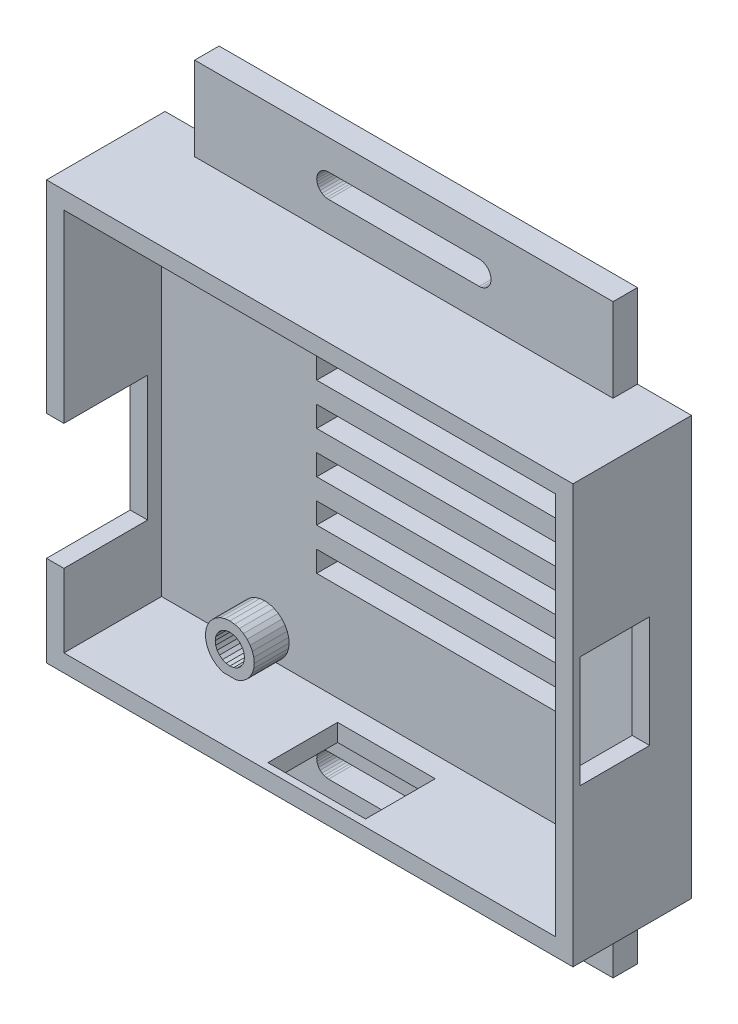
SolidWorks part; units mm, degrees
ref_plane "Front Plane" through (0, 0, 0) normal (0, 0, 1) x (1, 0, 0)
ref_plane "Top Plane" through (0, 0, 0) normal (0, 1, 0) x (1, 0, 0)
ref_plane "Right Plane" through (0, 0, 0) normal (1, 0, 0) x (0, 0, -1)
ref_plane "Plane1" through (0, 0, 0) normal (0, 0, -1) x (-1, 0, 0)
sketch "Sketch1" plane through (0, 0, 0) normal (0, 0, -1) x (-1, 0, 0)
  line L0 (37.75, 30) -> (-37.75, 30)
  line L1 (-37.75, 30) -> (-37.75, -30)
  line L2 (-37.75, -30) -> (37.75, -30)
  line L3 (37.75, -30) -> (37.75, 30)
extrude "Boss-Extrude1" add sketch "Sketch1" against normal blind 17
sketch "Sketch2" plane through (0, 0, 17) normal (0, 0, 1) x (1, 0, 0)
  line L0 (-35.25, -27.5) -> (35.25, -27.5)
  line L1 (35.25, -27.5) -> (35.25, 27.5)
  line L2 (35.25, 27.5) -> (-35.25, 27.5)
  line L3 (-35.25, 27.5) -> (-35.25, -27.5)
extrude "Cut-Extrude1" cut sketch "Sketch2" against normal blind 14
sketch "Sketch3" plane through (-37.75, 0, 0) normal (-1, 0, 0) x (0, 0, 1)
  line L0 (17, -17) -> (17, 1)
  line L1 (17, 1) -> (5, 1)
  line L2 (5, 1) -> (5, -17)
  line L3 (5, -17) -> (17, -17)
extrude "Cut-Extrude2" cut sketch "Sketch3" against normal up to next
sketch "Sketch4" plane through (0, 30, 0) normal (0, 1, 0) x (-1, 0, 0)
  line L0 (-30, 3.5) -> (30, 3.5)
  line L1 (30, 3.5) -> (30, 0)
  line L2 (30, 0) -> (-30, 0)
  line L3 (-30, 0) -> (-30, 3.5)
extrude "Boss-Extrude2" add sketch "Sketch4" along normal blind 12
sketch "Sketch5" plane through (0, 0, 3.5) normal (0, 0, 1) x (1, 0, 0)
  line L0 (12.3706, 36.6506) -> (12.2135, 36.9445)
  line L1 (12.2135, 36.9445) -> (12.0021, 37.2021)
  line L2 (12.0021, 37.2021) -> (11.7445, 37.4135)
  line L3 (11.7445, 37.4135) -> (11.4506, 37.5706)
  line L4 (11.4506, 37.5706) -> (11.1317, 37.6673)
  line L5 (11.1317, 37.6673) -> (10.8, 37.7)
  line L6 (10.8, 37.7) -> (-10.8, 37.7)
  line L7 (-10.8, 37.7) -> (-11.1317, 37.6673)
  line L8 (-11.1317, 37.6673) -> (-11.4506, 37.5706)
  line L9 (-11.4506, 37.5706) -> (-11.7445, 37.4135)
  line L10 (-11.7445, 37.4135) -> (-12.0021, 37.2021)
  line L11 (-12.0021, 37.2021) -> (-12.2135, 36.9445)
  line L12 (-12.2135, 36.9445) -> (-12.3706, 36.6506)
  line L13 (-12.3706, 36.6506) -> (-12.4673, 36.3317)
  line L14 (-12.4673, 36.3317) -> (-12.5, 36)
  line L15 (-12.5, 36) -> (-12.4673, 35.6683)
  line L16 (-12.4673, 35.6683) -> (-12.3706, 35.3494)
  line L17 (-12.3706, 35.3494) -> (-12.2135, 35.0555)
  line L18 (-12.2135, 35.0555) -> (-12.0021, 34.7979)
  line L19 (-12.0021, 34.7979) -> (-11.7445, 34.5865)
  line L20 (-11.7445, 34.5865) -> (-11.4506, 34.4294)
  line L21 (-11.4506, 34.4294) -> (-11.1317, 34.3327)
  line L22 (-11.1317, 34.3327) -> (-10.8, 34.3)
  line L23 (-10.8, 34.3) -> (10.8, 34.3)
  line L24 (10.8, 34.3) -> (11.1317, 34.3327)
  line L25 (11.1317, 34.3327) -> (11.4506, 34.4294)
  line L26 (11.4506, 34.4294) -> (11.7445, 34.5865)
  line L27 (11.7445, 34.5865) -> (12.0021, 34.7979)
  line L28 (12.0021, 34.7979) -> (12.2135, 35.0555)
  line L29 (12.2135, 35.0555) -> (12.3706, 35.3494)
  line L30 (12.3706, 35.3494) -> (12.4673, 35.6683)
  line L31 (12.4673, 35.6683) -> (12.5, 36)
  line L32 (12.5, 36) -> (12.4673, 36.3317)
  line L33 (12.4673, 36.3317) -> (12.3706, 36.6506)
extrude "Cut-Extrude3" cut sketch "Sketch5" against normal through all
sketch "Sketch6" plane through (0, -30, 0) normal (0, -1, 0) x (1, 0, 0)
  line L0 (-30, 0) -> (-30, 3.5)
  line L1 (-30, 3.5) -> (30, 3.5)
  line L2 (30, 3.5) -> (30, 0)
  line L3 (30, 0) -> (-30, 0)
extrude "Boss-Extrude3" add sketch "Sketch6" along normal blind 12
sketch "Sketch7" plane through (0, 0, 3.5) normal (0, 0, 1) x (1, 0, 0)
  line L0 (12.5, -36) -> (12.4673, -35.6683)
  line L1 (12.4673, -35.6683) -> (12.3706, -35.3494)
  line L2 (12.3706, -35.3494) -> (12.2135, -35.0555)
  line L3 (12.2135, -35.0555) -> (12.0021, -34.7979)
  line L4 (12.0021, -34.7979) -> (11.7445, -34.5865)
  line L5 (11.7445, -34.5865) -> (11.4506, -34.4294)
  line L6 (11.4506, -34.4294) -> (11.1317, -34.3327)
  line L7 (11.1317, -34.3327) -> (10.8, -34.3)
  line L8 (10.8, -34.3) -> (-10.8, -34.3)
  line L9 (-10.8, -34.3) -> (-11.1317, -34.3327)
  line L10 (-11.1317, -34.3327) -> (-11.4506, -34.4294)
  line L11 (-11.4506, -34.4294) -> (-11.7445, -34.5865)
  line L12 (-11.7445, -34.5865) -> (-12.0021, -34.7979)
  line L13 (-12.0021, -34.7979) -> (-12.2135, -35.0555)
  line L14 (-12.2135, -35.0555) -> (-12.3706, -35.3494)
  line L15 (-12.3706, -35.3494) -> (-12.4673, -35.6683)
  line L16 (-12.4673, -35.6683) -> (-12.5, -36)
  line L17 (-12.5, -36) -> (-12.4673, -36.3317)
  line L18 (-12.4673, -36.3317) -> (-12.3706, -36.6506)
  line L19 (-12.3706, -36.6506) -> (-12.2135, -36.9445)
  line L20 (-12.2135, -36.9445) -> (-12.0021, -37.2021)
  line L21 (-12.0021, -37.2021) -> (-11.7445, -37.4135)
  line L22 (-11.7445, -37.4135) -> (-11.4506, -37.5706)
  line L23 (-11.4506, -37.5706) -> (-11.1317, -37.6673)
  line L24 (-11.1317, -37.6673) -> (-10.8, -37.7)
  line L25 (-10.8, -37.7) -> (10.8, -37.7)
  line L26 (10.8, -37.7) -> (11.1317, -37.6673)
  line L27 (11.1317, -37.6673) -> (11.4506, -37.5706)
  line L28 (11.4506, -37.5706) -> (11.7445, -37.4135)
  line L29 (11.7445, -37.4135) -> (12.0021, -37.2021)
  line L30 (12.0021, -37.2021) -> (12.2135, -36.9445)
  line L31 (12.2135, -36.9445) -> (12.3706, -36.6506)
  line L32 (12.3706, -36.6506) -> (12.4673, -36.3317)
  line L33 (12.4673, -36.3317) -> (12.5, -36)
extrude "Cut-Extrude4" cut sketch "Sketch7" against normal through all
sketch "Sketch8" plane through (0, 0, 3) normal (0, 0, 1) x (1, 0, 0)
  line L0 (-13, 19.5) -> (-13, 16.5)
  line L1 (-13, 16.5) -> (23, 16.5)
  line L2 (23, 16.5) -> (23, 19.5)
  line L3 (23, 19.5) -> (-13, 19.5)
extrude "Cut-Extrude5" cut sketch "Sketch8" against normal through all
sketch "Sketch9" plane through (0, 0, 3) normal (0, 0, 1) x (1, 0, 0)
  line L0 (-13, -4.5) -> (-13, -7.5)
  line L1 (-13, -7.5) -> (23, -7.5)
  line L2 (23, -7.5) -> (23, -4.5)
  line L3 (23, -4.5) -> (-13, -4.5)
extrude "Cut-Extrude6" cut sketch "Sketch9" against normal through all
sketch "Sketch10" plane through (0, 0, 3) normal (0, 0, 1) x (1, 0, 0)
  line L0 (-13, 13.5) -> (-13, 10.5)
  line L1 (-13, 10.5) -> (23, 10.5)
  line L2 (23, 10.5) -> (23, 13.5)
  line L3 (23, 13.5) -> (-13, 13.5)
extrude "Cut-Extrude7" cut sketch "Sketch10" against normal through all
sketch "Sketch11" plane through (0, 0, 3) normal (0, 0, 1) x (1, 0, 0)
  line L0 (-13, 7.5) -> (-13, 4.5)
  line L1 (-13, 4.5) -> (23, 4.5)
  line L2 (23, 4.5) -> (23, 7.5)
  line L3 (23, 7.5) -> (-13, 7.5)
extrude "Cut-Extrude8" cut sketch "Sketch11" against normal through all
sketch "Sketch12" plane through (0, 0, 3) normal (0, 0, 1) x (1, 0, 0)
  line L0 (23, -13.5) -> (23, -10.5)
  line L1 (23, -10.5) -> (-13, -10.5)
  line L2 (-13, -10.5) -> (-13, -13.5)
  line L3 (-13, -13.5) -> (23, -13.5)
extrude "Cut-Extrude9" cut sketch "Sketch12" against normal through all
sketch "Sketch13" plane through (0, 0, 3) normal (0, 0, 1) x (1, 0, 0)
  line L0 (23, 1.5) -> (-13, 1.5)
  line L1 (-13, 1.5) -> (-13, -1.5)
  line L2 (-13, -1.5) -> (23, -1.5)
  line L3 (23, -1.5) -> (23, 1.5)
extrude "Cut-Extrude10" cut sketch "Sketch13" against normal through all
sketch "Sketch14" plane through (35.25, 0, 0) normal (-1, 0, 0) x (0, 0, 1)
  line L0 (6, 8) -> (6, -8)
  line L1 (6, -8) -> (16, -8)
  line L2 (16, -8) -> (16, 8)
  line L3 (16, 8) -> (6, 8)
extrude "Cut-Extrude11" cut sketch "Sketch14" against normal through all
sketch "Sketch15" plane through (0, -30, 0) normal (0, -1, 0) x (1, 0, 0)
  line L0 (7, 16) -> (-7, 16)
  line L1 (-7, 16) -> (-7, 6)
  line L2 (-7, 6) -> (7, 6)
  line L3 (7, 6) -> (7, 16)
extrude "Cut-Extrude12" cut sketch "Sketch15" against normal up to next
sketch "Sketch16" plane through (0, 0, 3) normal (0, 0, 1) x (1, 0, 0)
  line L0 (28.115, 8.89) -> (28.1823, 9.5728)
  line L1 (28.1823, 9.5728) -> (28.3814, 10.2294)
  line L2 (28.3814, 10.2294) -> (28.7049, 10.8345)
  line L3 (28.7049, 10.8345) -> (29.1401, 11.3649)
  line L4 (29.1401, 11.3649) -> (29.6705, 11.8001)
  line L5 (29.6705, 11.8001) -> (30.2756, 12.1236)
  line L6 (30.2756, 12.1236) -> (30.9322, 12.3227)
  line L7 (30.9322, 12.3227) -> (31.615, 12.39)
  line L8 (31.615, 12.39) -> (32.2978, 12.3227)
  line L9 (32.2978, 12.3227) -> (32.9544, 12.1236)
  line L10 (32.9544, 12.1236) -> (33.5595, 11.8001)
  line L11 (33.5595, 11.8001) -> (34.0899, 11.3649)
  line L12 (34.0899, 11.3649) -> (34.5251, 10.8345)
  line L13 (34.5251, 10.8345) -> (34.8486, 10.2294)
  line L14 (34.8486, 10.2294) -> (35.0477, 9.5728)
  line L15 (35.0477, 9.5728) -> (35.115, 8.89)
  line L16 (35.115, 8.89) -> (35.0477, 8.2072)
  line L17 (35.0477, 8.2072) -> (34.8486, 7.5506)
  line L18 (34.8486, 7.5506) -> (34.5251, 6.9455)
  line L19 (34.5251, 6.9455) -> (34.0899, 6.4151)
  line L20 (34.0899, 6.4151) -> (33.5595, 5.9799)
  line L21 (33.5595, 5.9799) -> (32.9544, 5.6564)
  line L22 (32.9544, 5.6564) -> (32.2978, 5.4573)
  line L23 (32.2978, 5.4573) -> (31.615, 5.39)
  line L24 (31.615, 5.39) -> (30.9322, 5.4573)
  line L25 (30.9322, 5.4573) -> (30.2756, 5.6564)
  line L26 (30.2756, 5.6564) -> (29.6705, 5.9799)
  line L27 (29.6705, 5.9799) -> (29.1401, 6.4151)
  line L28 (29.1401, 6.4151) -> (28.7049, 6.9455)
  line L29 (28.7049, 6.9455) -> (28.3814, 7.5506)
  line L30 (28.3814, 7.5506) -> (28.1823, 8.2072)
  line L31 (28.1823, 8.2072) -> (28.115, 8.89)
extrude "Boss-Extrude4" add sketch "Sketch16" along normal blind 5
sketch "Sketch17" plane through (0, 0, 8) normal (0, 0, 1) x (1, 0, 0)
  line L0 (29.5866, 9.4335) -> (29.515, 8.89)
  line L1 (29.515, 8.89) -> (29.5866, 8.3465)
  line L2 (29.5866, 8.3465) -> (29.7963, 7.84)
  line L3 (29.7963, 7.84) -> (30.1301, 7.4051)
  line L4 (30.1301, 7.4051) -> (30.565, 7.0713)
  line L5 (30.565, 7.0713) -> (31.0715, 6.8616)
  line L6 (31.0715, 6.8616) -> (31.615, 6.79)
  line L7 (31.615, 6.79) -> (32.1585, 6.8616)
  line L8 (32.1585, 6.8616) -> (32.665, 7.0713)
  line L9 (32.665, 7.0713) -> (33.0999, 7.4051)
  line L10 (33.0999, 7.4051) -> (33.4337, 7.84)
  line L11 (33.4337, 7.84) -> (33.6434, 8.3465)
  line L12 (33.6434, 8.3465) -> (33.715, 8.89)
  line L13 (33.715, 8.89) -> (33.6434, 9.4335)
  line L14 (33.6434, 9.4335) -> (33.4337, 9.94)
  line L15 (33.4337, 9.94) -> (33.0999, 10.3749)
  line L16 (33.0999, 10.3749) -> (32.665, 10.7087)
  line L17 (32.665, 10.7087) -> (32.1585, 10.9184)
  line L18 (32.1585, 10.9184) -> (31.615, 10.99)
  line L19 (31.615, 10.99) -> (31.0715, 10.9184)
  line L20 (31.0715, 10.9184) -> (30.565, 10.7087)
  line L21 (30.565, 10.7087) -> (30.1301, 10.3749)
  line L22 (30.1301, 10.3749) -> (29.7963, 9.94)
  line L23 (29.7963, 9.94) -> (29.5866, 9.4335)
extrude "Cut-Extrude13" cut sketch "Sketch17" against normal blind 5.5
sketch "Sketch18" plane through (0, 0, 3) normal (0, 0, 1) x (1, 0, 0)
  line L0 (-20.5244, 27.3636) -> (-20.0747, 27.5)
  line L1 (-20.0747, 27.5) -> (-18.2953, 27.5)
  line L2 (-18.2953, 27.5) -> (-17.8456, 27.3636)
  line L3 (-17.8456, 27.3636) -> (-17.2405, 27.0401)
  line L4 (-17.2405, 27.0401) -> (-16.7101, 26.6049)
  line L5 (-16.7101, 26.6049) -> (-16.2749, 26.0745)
  line L6 (-16.2749, 26.0745) -> (-15.9514, 25.4694)
  line L7 (-15.9514, 25.4694) -> (-15.7523, 24.8128)
  line L8 (-15.7523, 24.8128) -> (-15.685, 24.13)
  line L9 (-15.685, 24.13) -> (-15.7523, 23.4472)
  line L10 (-15.7523, 23.4472) -> (-15.9514, 22.7906)
  line L11 (-15.9514, 22.7906) -> (-16.2749, 22.1855)
  line L12 (-16.2749, 22.1855) -> (-16.7101, 21.6551)
  line L13 (-16.7101, 21.6551) -> (-17.2405, 21.2199)
  line L14 (-17.2405, 21.2199) -> (-17.8456, 20.8964)
  line L15 (-17.8456, 20.8964) -> (-18.5022, 20.6973)
  line L16 (-18.5022, 20.6973) -> (-19.185, 20.63)
  line L17 (-19.185, 20.63) -> (-19.8678, 20.6973)
  line L18 (-19.8678, 20.6973) -> (-20.5244, 20.8964)
  line L19 (-20.5244, 20.8964) -> (-21.1295, 21.2199)
  line L20 (-21.1295, 21.2199) -> (-21.6599, 21.6551)
  line L21 (-21.6599, 21.6551) -> (-22.0951, 22.1855)
  line L22 (-22.0951, 22.1855) -> (-22.4186, 22.7906)
  line L23 (-22.4186, 22.7906) -> (-22.6177, 23.4472)
  line L24 (-22.6177, 23.4472) -> (-22.685, 24.13)
  line L25 (-22.685, 24.13) -> (-22.6177, 24.8128)
  line L26 (-22.6177, 24.8128) -> (-22.4186, 25.4694)
  line L27 (-22.4186, 25.4694) -> (-22.0951, 26.0745)
  line L28 (-22.0951, 26.0745) -> (-21.6599, 26.6049)
  line L29 (-21.6599, 26.6049) -> (-21.1295, 27.0401)
  line L30 (-21.1295, 27.0401) -> (-20.5244, 27.3636)
extrude "Boss-Extrude5" add sketch "Sketch18" along normal blind 5
sketch "Sketch19" plane through (0, 0, 8) normal (0, 0, 1) x (1, 0, 0)
  line L0 (-21.0037, 23.08) -> (-20.6699, 22.6451)
  line L1 (-20.6699, 22.6451) -> (-20.235, 22.3113)
  line L2 (-20.235, 22.3113) -> (-19.7285, 22.1016)
  line L3 (-19.7285, 22.1016) -> (-19.185, 22.03)
  line L4 (-19.185, 22.03) -> (-18.6415, 22.1016)
  line L5 (-18.6415, 22.1016) -> (-18.135, 22.3113)
  line L6 (-18.135, 22.3113) -> (-17.7001, 22.6451)
  line L7 (-17.7001, 22.6451) -> (-17.3663, 23.08)
  line L8 (-17.3663, 23.08) -> (-17.1566, 23.5865)
  line L9 (-17.1566, 23.5865) -> (-17.085, 24.13)
  line L10 (-17.085, 24.13) -> (-17.1566, 24.6735)
  line L11 (-17.1566, 24.6735) -> (-17.3663, 25.18)
  line L12 (-17.3663, 25.18) -> (-17.7001, 25.6149)
  line L13 (-17.7001, 25.6149) -> (-18.135, 25.9487)
  line L14 (-18.135, 25.9487) -> (-18.6415, 26.1584)
  line L15 (-18.6415, 26.1584) -> (-19.185, 26.23)
  line L16 (-19.185, 26.23) -> (-19.7285, 26.1584)
  line L17 (-19.7285, 26.1584) -> (-20.235, 25.9487)
  line L18 (-20.235, 25.9487) -> (-20.6699, 25.6149)
  line L19 (-20.6699, 25.6149) -> (-21.0037, 25.18)
  line L20 (-21.0037, 25.18) -> (-21.2134, 24.6735)
  line L21 (-21.2134, 24.6735) -> (-21.285, 24.13)
  line L22 (-21.285, 24.13) -> (-21.2134, 23.5865)
  line L23 (-21.2134, 23.5865) -> (-21.0037, 23.08)
extrude "Cut-Extrude14" cut sketch "Sketch19" against normal blind 5.5
sketch "Sketch20" plane through (0, 0, 3) normal (0, 0, 1) x (1, 0, 0)
  line L0 (34.0899, -16.5751) -> (34.5251, -17.1055)
  line L1 (34.5251, -17.1055) -> (34.8486, -17.7106)
  line L2 (34.8486, -17.7106) -> (35.0477, -18.3672)
  line L3 (35.0477, -18.3672) -> (35.115, -19.05)
  line L4 (35.115, -19.05) -> (35.0477, -19.7328)
  line L5 (35.0477, -19.7328) -> (34.8486, -20.3894)
  line L6 (34.8486, -20.3894) -> (34.5251, -20.9945)
  line L7 (34.5251, -20.9945) -> (34.0899, -21.5249)
  line L8 (34.0899, -21.5249) -> (33.5595, -21.9601)
  line L9 (33.5595, -21.9601) -> (32.9544, -22.2836)
  line L10 (32.9544, -22.2836) -> (32.2978, -22.4827)
  line L11 (32.2978, -22.4827) -> (31.615, -22.55)
  line L12 (31.615, -22.55) -> (30.9322, -22.4827)
  line L13 (30.9322, -22.4827) -> (30.2756, -22.2836)
  line L14 (30.2756, -22.2836) -> (29.6705, -21.9601)
  line L15 (29.6705, -21.9601) -> (29.1401, -21.5249)
  line L16 (29.1401, -21.5249) -> (28.7049, -20.9945)
  line L17 (28.7049, -20.9945) -> (28.3814, -20.3894)
  line L18 (28.3814, -20.3894) -> (28.1823, -19.7328)
  line L19 (28.1823, -19.7328) -> (28.115, -19.05)
  line L20 (28.115, -19.05) -> (28.1823, -18.3672)
  line L21 (28.1823, -18.3672) -> (28.3814, -17.7106)
  line L22 (28.3814, -17.7106) -> (28.7049, -17.1055)
  line L23 (28.7049, -17.1055) -> (29.1401, -16.5751)
  line L24 (29.1401, -16.5751) -> (29.6705, -16.1399)
  line L25 (29.6705, -16.1399) -> (30.2756, -15.8164)
  line L26 (30.2756, -15.8164) -> (30.9322, -15.6173)
  line L27 (30.9322, -15.6173) -> (31.615, -15.55)
  line L28 (31.615, -15.55) -> (32.2978, -15.6173)
  line L29 (32.2978, -15.6173) -> (32.9544, -15.8164)
  line L30 (32.9544, -15.8164) -> (33.5595, -16.1399)
  line L31 (33.5595, -16.1399) -> (34.0899, -16.5751)
extrude "Boss-Extrude6" add sketch "Sketch20" along normal blind 5
sketch "Sketch21" plane through (0, 0, 8) normal (0, 0, 1) x (1, 0, 0)
  line L0 (31.615, -16.95) -> (31.0715, -17.0216)
  line L1 (31.0715, -17.0216) -> (30.565, -17.2313)
  line L2 (30.565, -17.2313) -> (30.1301, -17.5651)
  line L3 (30.1301, -17.5651) -> (29.7963, -18)
  line L4 (29.7963, -18) -> (29.5866, -18.5065)
  line L5 (29.5866, -18.5065) -> (29.515, -19.05)
  line L6 (29.515, -19.05) -> (29.5866, -19.5935)
  line L7 (29.5866, -19.5935) -> (29.7963, -20.1)
  line L8 (29.7963, -20.1) -> (30.1301, -20.5349)
  line L9 (30.1301, -20.5349) -> (30.565, -20.8687)
  line L10 (30.565, -20.8687) -> (31.0715, -21.0784)
  line L11 (31.0715, -21.0784) -> (31.615, -21.15)
  line L12 (31.615, -21.15) -> (32.1585, -21.0784)
  line L13 (32.1585, -21.0784) -> (32.665, -20.8687)
  line L14 (32.665, -20.8687) -> (33.0999, -20.5349)
  line L15 (33.0999, -20.5349) -> (33.4337, -20.1)
  line L16 (33.4337, -20.1) -> (33.6434, -19.5935)
  line L17 (33.6434, -19.5935) -> (33.715, -19.05)
  line L18 (33.715, -19.05) -> (33.6434, -18.5065)
  line L19 (33.6434, -18.5065) -> (33.4337, -18)
  line L20 (33.4337, -18) -> (33.0999, -17.5651)
  line L21 (33.0999, -17.5651) -> (32.665, -17.2313)
  line L22 (32.665, -17.2313) -> (32.1585, -17.0216)
  line L23 (32.1585, -17.0216) -> (31.615, -16.95)
extrude "Cut-Extrude15" cut sketch "Sketch21" against normal blind 5.5
sketch "Sketch22" plane through (0, 0, 3) normal (0, 0, 1) x (1, 0, 0)
  line L0 (-19.1156, -27.3636) -> (-19.5653, -27.5)
  line L1 (-19.5653, -27.5) -> (-21.3447, -27.5)
  line L2 (-21.3447, -27.5) -> (-21.7944, -27.3636)
  line L3 (-21.7944, -27.3636) -> (-22.3995, -27.0401)
  line L4 (-22.3995, -27.0401) -> (-22.9299, -26.6049)
  line L5 (-22.9299, -26.6049) -> (-23.3651, -26.0745)
  line L6 (-23.3651, -26.0745) -> (-23.6886, -25.4694)
  line L7 (-23.6886, -25.4694) -> (-23.8877, -24.8128)
  line L8 (-23.8877, -24.8128) -> (-23.955, -24.13)
  line L9 (-23.955, -24.13) -> (-23.8877, -23.4472)
  line L10 (-23.8877, -23.4472) -> (-23.6886, -22.7906)
  line L11 (-23.6886, -22.7906) -> (-23.3651, -22.1855)
  line L12 (-23.3651, -22.1855) -> (-22.9299, -21.6551)
  line L13 (-22.9299, -21.6551) -> (-22.3995, -21.2199)
  line L14 (-22.3995, -21.2199) -> (-21.7944, -20.8964)
  line L15 (-21.7944, -20.8964) -> (-21.1378, -20.6973)
  line L16 (-21.1378, -20.6973) -> (-20.455, -20.63)
  line L17 (-20.455, -20.63) -> (-19.7722, -20.6973)
  line L18 (-19.7722, -20.6973) -> (-19.1156, -20.8964)
  line L19 (-19.1156, -20.8964) -> (-18.5105, -21.2199)
  line L20 (-18.5105, -21.2199) -> (-17.9801, -21.6551)
  line L21 (-17.9801, -21.6551) -> (-17.5449, -22.1855)
  line L22 (-17.5449, -22.1855) -> (-17.2214, -22.7906)
  line L23 (-17.2214, -22.7906) -> (-17.0223, -23.4472)
  line L24 (-17.0223, -23.4472) -> (-16.955, -24.13)
  line L25 (-16.955, -24.13) -> (-17.0223, -24.8128)
  line L26 (-17.0223, -24.8128) -> (-17.2214, -25.4694)
  line L27 (-17.2214, -25.4694) -> (-17.5449, -26.0745)
  line L28 (-17.5449, -26.0745) -> (-17.9801, -26.6049)
  line L29 (-17.9801, -26.6049) -> (-18.5105, -27.0401)
  line L30 (-18.5105, -27.0401) -> (-19.1156, -27.3636)
extrude "Boss-Extrude7" add sketch "Sketch22" along normal blind 5
sketch "Sketch23" plane through (0, 0, 8) normal (0, 0, 1) x (1, 0, 0)
  line L0 (-22.4834, -23.5865) -> (-22.555, -24.13)
  line L1 (-22.555, -24.13) -> (-22.4834, -24.6735)
  line L2 (-22.4834, -24.6735) -> (-22.2737, -25.18)
  line L3 (-22.2737, -25.18) -> (-21.9399, -25.6149)
  line L4 (-21.9399, -25.6149) -> (-21.505, -25.9487)
  line L5 (-21.505, -25.9487) -> (-20.9985, -26.1584)
  line L6 (-20.9985, -26.1584) -> (-20.455, -26.23)
  line L7 (-20.455, -26.23) -> (-19.9115, -26.1584)
  line L8 (-19.9115, -26.1584) -> (-19.405, -25.9487)
  line L9 (-19.405, -25.9487) -> (-18.9701, -25.6149)
  line L10 (-18.9701, -25.6149) -> (-18.6363, -25.18)
  line L11 (-18.6363, -25.18) -> (-18.4266, -24.6735)
  line L12 (-18.4266, -24.6735) -> (-18.355, -24.13)
  line L13 (-18.355, -24.13) -> (-18.4266, -23.5865)
  line L14 (-18.4266, -23.5865) -> (-18.6363, -23.08)
  line L15 (-18.6363, -23.08) -> (-18.9701, -22.6451)
  line L16 (-18.9701, -22.6451) -> (-19.405, -22.3113)
  line L17 (-19.405, -22.3113) -> (-19.9115, -22.1016)
  line L18 (-19.9115, -22.1016) -> (-20.455, -22.03)
  line L19 (-20.455, -22.03) -> (-20.9985, -22.1016)
  line L20 (-20.9985, -22.1016) -> (-21.505, -22.3113)
  line L21 (-21.505, -22.3113) -> (-21.9399, -22.6451)
  line L22 (-21.9399, -22.6451) -> (-22.2737, -23.08)
  line L23 (-22.2737, -23.08) -> (-22.4834, -23.5865)
extrude "Cut-Extrude16" cut sketch "Sketch23" against normal blind 5.5
